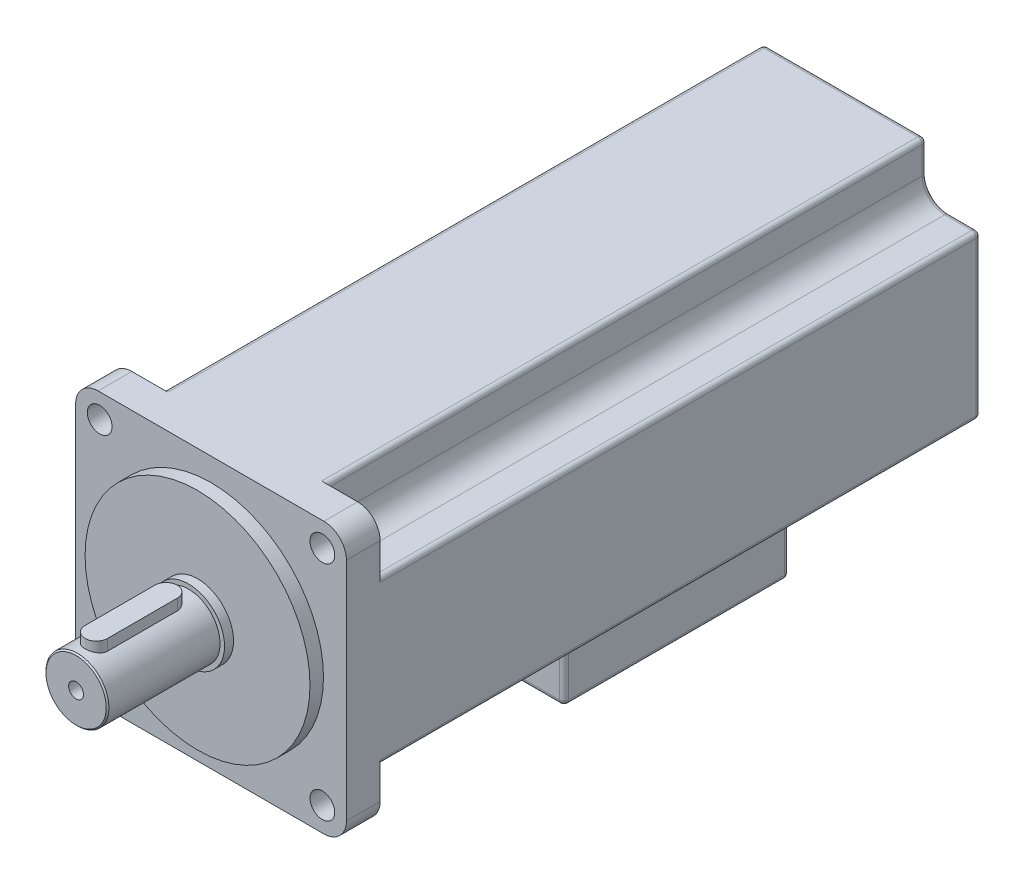
SolidWorks part; units mm, degrees
ref_plane "前视基准面" through (0, 0, 0) normal (0, 0, 1) x (1, 0, 0)
ref_plane "上视基准面" through (0, 0, 0) normal (0, 1, 0) x (1, 0, 0)
ref_plane "右视基准面" through (0, 0, 0) normal (1, 0, 0) x (0, 0, -1)
sketch "草图1" plane through (0, 0, 0) normal (0, 0, 1) x (1, 0, 0)
  line L1 (-30.1, -30.1) -> (30.1, -30.1)
  line L2 (-30.1, -30.1) -> (-30.1, 30.1)
  line L3 (-30.1, 30.1) -> (30.1, 30.1)
  line L4 (30.1, -30.1) -> (30.1, 30.1)
  line L5 (-30.1, -30.1) -> (30.1, 30.1) construction
  line L6 (-30.1, 30.1) -> (30.1, -30.1) construction
  point P0 (0, 0)
  dimension "D1" = 60.2
  dimension "D2" = 60.2
extrude "凸台-拉伸1" add sketch "草图1" along normal blind 7.5
fillet "圆角1" radius 5 4 edges at (-30.1, -30.1, 3.75) (30.1, -30.1, 3.75) (30.1, 30.1, 3.75) (-30.1, 30.1, 3.75)
sketch "草图2" plane through (0, 0, 7.5) normal (0, 0, 1) x (1, 0, 0)
  line L1 (-24.7487, 24.7487) -> (24.7487, 24.7487) construction
  line L2 (-24.7487, 24.7487) -> (-24.7487, -24.7487) construction
  line L3 (-24.7487, -24.7487) -> (24.7487, -24.7487) construction
  line L4 (24.7487, 24.7487) -> (24.7487, -24.7487) construction
  line L5 (-24.7487, 24.7487) -> (24.7487, -24.7487) construction
  line L6 (-24.7487, -24.7487) -> (24.7487, 24.7487) construction
  circle A0 centre (0, 0) radius 35 construction
  circle A1 centre (-24.7487, 24.7487) radius 2.75
  circle A2 centre (24.7487, 24.7487) radius 2.75
  circle A3 centre (24.7487, -24.7487) radius 2.75
  circle A4 centre (-24.7487, -24.7487) radius 2.75
  dimension "D1" = 70
  dimension "D2" = 5.5
extrude "切除-拉伸1" cut sketch "草图2" against normal through all
sketch "草图3" plane through (0, 0, 7.5) normal (0, 0, 1) x (1, 0, 0)
  circle A0 centre (0, 0) radius 25
  dimension "D1" = 50
extrude "凸台-拉伸2" add sketch "草图3" along normal blind 3
sketch "草图4" plane through (0, 0, 10.5) normal (0, 0, 1) x (1, 0, 0)
  circle A0 centre (0, 0) radius 8
  dimension "D1" = 16
extrude "凸台-拉伸3" add sketch "草图4" along normal blind 2
sketch "草图5" plane through (0, 0, 12.5) normal (0, 0, 1) x (1, 0, 0)
  circle A0 centre (0, 0) radius 7
  dimension "D1" = 14
extrude "凸台-拉伸4" add sketch "草图5" along normal blind 25
hole_wizard "M4 螺纹孔2" positions "草图8" profile "草图9" tap size "M4" standard "ISO"
sketch "草图8" plane through (0, 0, 37.5) normal (0, 0, 1) x (1, 0, 0)
  point P0 (0, 0)
sketch "草图9" plane through (0, 0, 37.5) normal (1, 0, 0) x (0, -1, 0)
  line L0 (0, 0) -> (0, 11.0914)
  line L1 (0, 11.0914) -> (1.65, 10.1)
  line L2 (1.65, 10.1) -> (1.65, 0)
  line L5 (1.65, 0) -> (0, 0)
  line L10 (0, 11.0914) -> (-1.65, 10.1) construction
  line L11 (0, -6.35) -> (0, 107.95) construction
  dimension "螺纹孔钻头直径" = 3.3
  dimension "螺纹孔钻头深度" = 10.1
  dimension "导头角度" = 118
cosmetic thread "孔螺蚊线2" parameters "D1"=8, "D2"=4
chamfer "倒角1" distance 0.3 angle 45 1 edges at (7, 0, 37.5)
ref_plane "基准面1" through (0, 9, 0) normal (0, 1, 0) x (1, 0, 0)
sketch "草图10" plane through (0, 9, 0) normal (0, 1, 0) x (1, 0, 0)
  line L0 (0, -33) -> (0, -17.5) construction
  line L1 (-2.5, -33) -> (-2.5, -17.5)
  line L2 (2.5, -33) -> (2.5, -17.5)
  line L3 (-6.7, -37.5) -> (6.7, -37.5) construction
  arc A0 (-2.5, -33) -> (2.5, -33) centre (0, -33) ccw
  arc A1 (2.5, -17.5) -> (-2.5, -17.5) centre (0, -17.5) ccw
  point P3 (0, -25.25)
  point P10 (0, -35.5)
  point P11 (0, -15)
  dimension "D2" = 2.5
  dimension "D1" = 20.5
  dimension "D3" = 4.5
extrude "凸台-拉伸5" add sketch "草图10" against normal blind 5
sketch "草图12" plane through (0, 0, 0) normal (0, 0, -1) x (-1, 0, 0)
  line L0 (30.1, -18.1) -> (18.1, -18.1)
  line L1 (-18.1, -30.1) -> (18.1, -30.1)
  line L2 (-30.1, -18.1) -> (-30.1, 18.1)
  line L3 (-18.1, 30.1) -> (18.1, 30.1)
  line L4 (30.1, -18.1) -> (30.1, 18.1)
  line L5 (-23.9484, -23.9484) -> (29.92, 29.92) construction
  line L6 (-30.279, 30.279) -> (30.279, -30.279) construction
  line L7 (18.1, -18.1) -> (18.1, -30.1)
  line L8 (30.1, 18.1) -> (18.1, 18.1)
  line L9 (18.1, 18.1) -> (18.1, 30.1)
  line L10 (0, 0) -> (0, -11.5891) construction
  line L11 (-18.1, 18.1) -> (-18.1, 30.1)
  line L12 (-30.1, 18.1) -> (-18.1, 18.1)
  line L13 (-18.1, -18.1) -> (-18.1, -30.1)
  line L14 (-30.1, -18.1) -> (-18.1, -18.1)
  line L15 (30.1, 25.1) -> (30.1, -25.1) construction
  line L16 (25.1, -30.1) -> (-25.1, -30.1) construction
  point P0 (0, 0)
  point P20 (30.1, -17.7072)
  point P23 (-17.1812, -30.1)
  point P26 (-7.8893, 18.1)
  dimension "D1" = 60.2
  dimension "D2" = 60.2
  dimension "D3" = 12
  dimension "D4" = 60.2
extrude "凸台-拉伸6" add sketch "草图12" along normal blind 133.5
fillet "圆角2" radius 5 4 edges at (-18.1, -18.1, -66.75) (-18.1, 18.1, -66.75) (18.1, 18.1, -66.75) (18.1, -18.1, -66.75)
sketch "草图13" plane through (0, -30.1, 0) normal (0, -1, 0) x (1, 0, 0)
  line L0 (0, -133.5) -> (0, -88.5) construction
  line L1 (18.1, -133.5) -> (-18.1, -133.5) construction
  line L3 (7.5, -63.5) -> (-7.5, -63.5)
  line L4 (7.5, -63.5) -> (7.5, -113.5)
  line L5 (7.5, -113.5) -> (-7.5, -113.5)
  line L6 (-7.5, -63.5) -> (-7.5, -113.5)
  line L7 (7.5, -63.5) -> (-7.5, -113.5) construction
  line L8 (7.5, -113.5) -> (-7.5, -63.5) construction
  dimension "D1" = 45
  dimension "D2" = 15
  dimension "D3" = 50
extrude "凸台-拉伸7" add sketch "草图13" along normal blind 20
fillet "圆角3" radius 1 32 edges at (0, -50.1, -63.5) (7.5, -50.1, -88.5) (0, -50.1, -113.5) (-7.5, -50.1, -88.5) (-26.6, -18.1, -133.5) (-19.5645, -19.5645, -133.5) (-18.1, -26.6, -133.5) (0, -30.1, -133.5) (18.1, -26.6, -133.5) (19.5645, -19.5645, -133.5) (26.6, -18.1, -133.5) (30.1, 0, -133.5) (26.6, 18.1, -133.5) (19.5645, 19.5645, -133.5) (18.1, 26.6, -133.5) (0, 30.1, -133.5) (-18.1, 26.6, -133.5) (-19.5645, 19.5645, -133.5) (-26.6, 18.1, -133.5) (-30.1, 0, -133.5) (18.1, 30.1, -66.75) (-18.1, 30.1, -66.75) (-30.1, 18.1, -66.75) (-30.1, -18.1, -66.75) (-18.1, -30.1, -66.75) (30.1, -18.1, -66.75) (30.1, 18.1, -66.75) (7.5, -40.1, -63.5) (-7.5, -40.1, -63.5) (-7.5, -40.1, -113.5) (7.5, -40.1, -113.5) (18.1, -30.1, -66.75)
